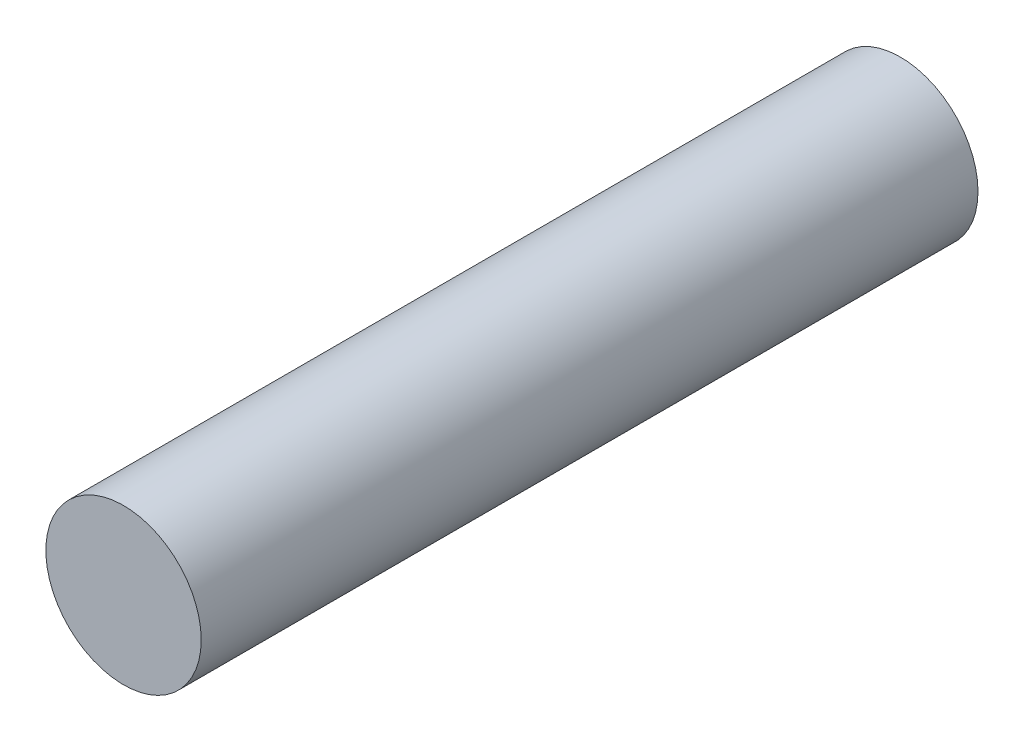
SolidWorks part; units mm, degrees
ref_plane "前视基准面" through (0, 0, 0) normal (0, 0, 1) x (1, 0, 0)
ref_plane "上视基准面" through (0, 0, 0) normal (0, 1, 0) x (1, 0, 0)
ref_plane "右视基准面" through (0, 0, 0) normal (1, 0, 0) x (0, 0, -1)
other "Configuration Table"
sketch "草图1" plane through (0, 0, 0) normal (0, 0, 1) x (1, 0, 0)
  circle A0 centre (0, 0) radius 6
  dimension "D1" = 12
extrude "凸台-拉伸1" add sketch "草图1" along normal mid plane 60
